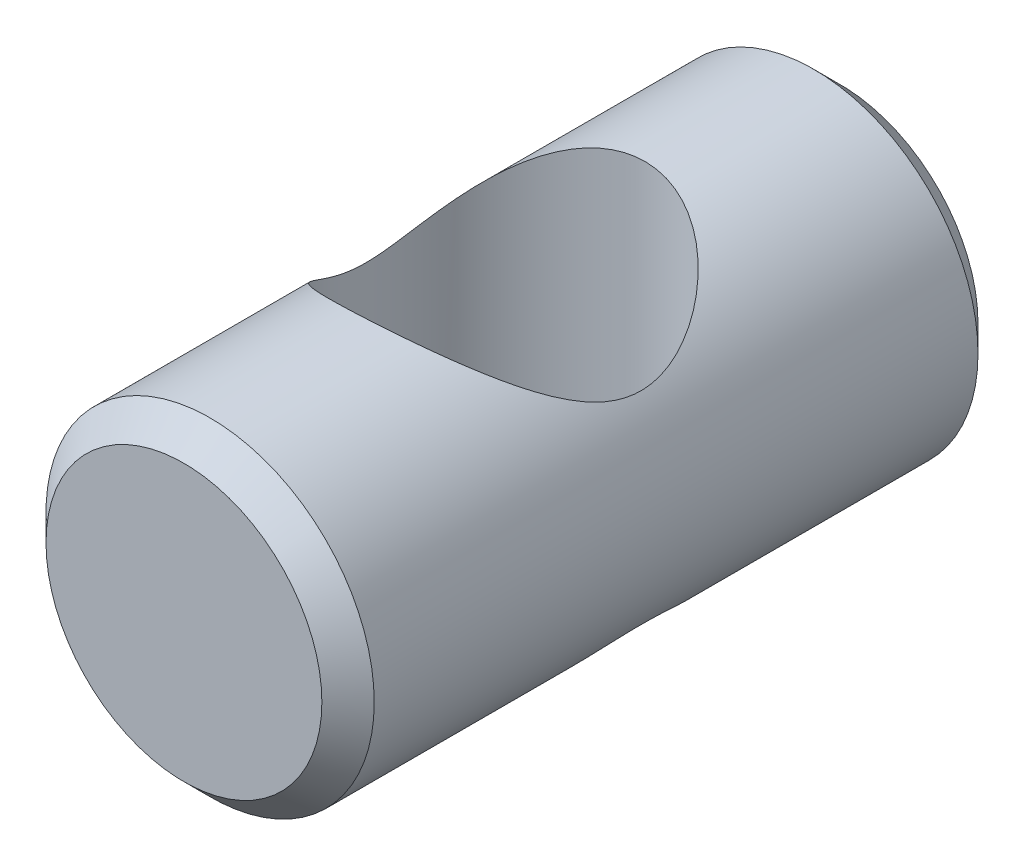
SolidWorks part; units mm, degrees
ref_plane "Front Plane" through (0, 0, 0) normal (0, 0, 1) x (1, 0, 0)
ref_plane "Top Plane" through (0, 0, 0) normal (0, 1, 0) x (1, 0, 0)
ref_plane "Right Plane" through (0, 0, 0) normal (1, 0, 0) x (0, 0, -1)
sketch "Sketch1" plane through (0, 0, 0) normal (0, 0, 1) x (1, 0, 0)
  circle A0 centre (0, 0) radius 4.765
  dimension "D1" = 9.53
extrude "Boss-Extrude1" add sketch "Sketch1" along normal mid plane 19.05
chamfer "Chamfer1" distance 0.76 angle 45 2 edges at (4.765, 0, -9.525) (4.765, 0, 9.525)
sketch "Sketch2" plane through (0, 0, 0) normal (0, 1, 0) x (1, 0, 0)
  circle A0 centre (-0.25, 0) radius 4
  dimension "D1" = 8
  dimension "D2" = 0.25
extrude "Cut-Extrude1" cut sketch "Sketch2" against normal through all both and the other way through all
